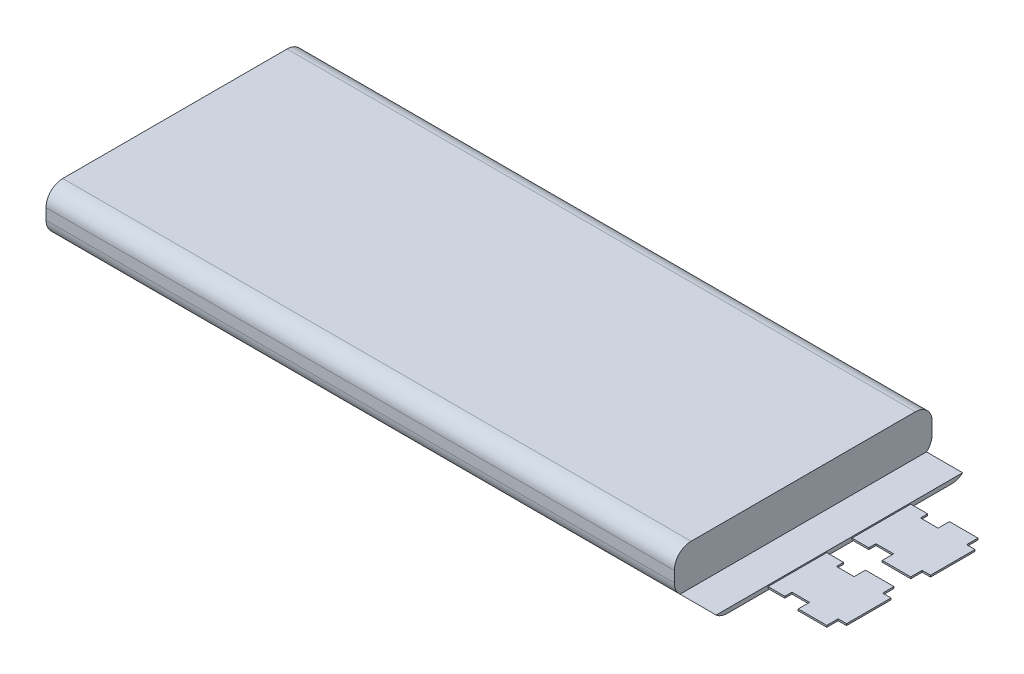
SolidWorks part; units mm, degrees
ref_plane "Front Plane" through (0, 0, 0) normal (0, 0, 1) x (1, 0, 0)
ref_plane "Top Plane" through (0, 0, 0) normal (0, 1, 0) x (1, 0, 0)
ref_plane "Right Plane" through (0, 0, 0) normal (1, 0, 0) x (0, 0, -1)
sketch "Sketch1" plane through (0, 0, 0) normal (0, 1, 0) x (1, 0, 0)
  line L1 (39.55, -15.35) -> (-39.55, -15.35)
  line L2 (39.55, -15.35) -> (39.55, 15.35)
  line L3 (39.55, 15.35) -> (-39.55, 15.35)
  line L4 (-39.55, -15.35) -> (-39.55, 15.35)
  line L5 (39.55, -15.35) -> (-39.55, 15.35) construction
  line L6 (39.55, 15.35) -> (-39.55, -15.35) construction
  point P0 (0, 0)
  dimension "D1" = 79.1
  dimension "D2" = 30.7
extrude "Boss-Extrude1" add sketch "Sketch1" along normal blind 5.3
fillet "Fillet1" radius 2 4 edges at (0, 0, -15.35) (0, 5.3, -15.35) (0, 0, 15.35) (0, 5.3, 15.35)
sketch "Sketch2" plane through (0, 5.3, 0) normal (0, 1, 0) x (1, 0, 0)
  line L0 (39.55, -15.35) -> (-39.55, -15.35) construction
  line L1 (39.55, 15.35) -> (35.25, 15.35)
  line L2 (39.55, 15.35) -> (39.55, -15.35)
  line L3 (39.55, -15.35) -> (35.25, -15.35)
  line L4 (35.25, 15.35) -> (35.25, -15.35)
  dimension "D1" = 4.3
extrude "Cut-Extrude1" cut sketch "Sketch2" against normal offset from surface (4.8 mm away) 0.5 up to face at (0, 0, 0)
ref_plane "Plane1" through (0, 0.25, 0) normal (0, 1, 0) x (1, 0, 0)
sketch "Sketch3" plane through (0, 0.25, 0) normal (0, 1, 0) x (1, 0, 0)
  line L0 (0, 0) -> (57.6181, 0) construction
  line L1 (39.55, 14.6729) -> (39.55, -14.6729) construction
  line L2 (39.55, 8.5) -> (41.55, 8.5)
  line L3 (39.55, 8.5) -> (39.55, 1.5)
  line L4 (39.55, 1.5) -> (41.55, 1.5)
  line L5 (41.55, 8.5) -> (41.55, 7.65)
  line L6 (45.35, 9) -> (45.35, 1) construction
  line L7 (41.55, 2.35) -> (43.65, 2.35)
  line L9 (41.55, 7.65) -> (43.65, 7.65)
  line L10 (48.05, 2.35) -> (48.05, 7.65)
  line L11 (47.05, 9) -> (43.65, 9)
  line L12 (47.05, 9) -> (47.05, 7.65)
  line L13 (47.05, 1) -> (43.65, 1)
  line L14 (43.65, 9) -> (43.65, 7.65)
  line L15 (48.05, 5) -> (41.55, 5) construction
  line L16 (41.55, 2.35) -> (41.55, 1.5)
  line L17 (43.65, 2.35) -> (43.65, 1)
  line L18 (47.05, 2.35) -> (48.05, 2.35)
  line L19 (47.05, 2.35) -> (47.05, 1)
  line L20 (41.55, 7.65) -> (41.55, 2.35) construction
  line L21 (47.05, 7.65) -> (48.05, 7.65)
  point P21 (41.55, 5)
  point P22 (45.35, 5)
  point P23 (41.8393, 5)
  dimension "D1" = 2
  dimension "D2" = 8
  dimension "D3" = 5.3
  dimension "D4" = 3.4
  dimension "D5" = 1
  dimension "D6" = 5.5
  dimension "D7" = 5
  dimension "D8" = 7
extrude "Boss-Extrude2" add sketch "Sketch3" along normal mid plane 0.2
mirror "Mirror1" about plane through (0, 0, 0) normal (0, 0, 1) of "Boss-Extrude2"
